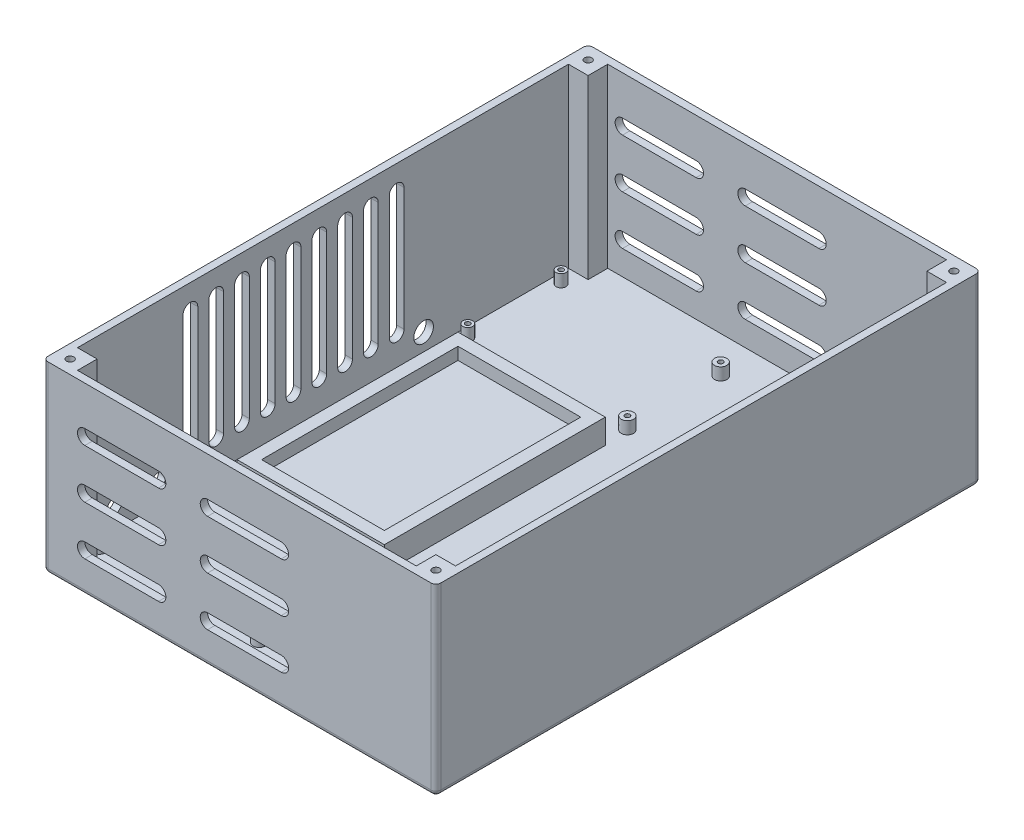
SolidWorks part; units mm, degrees
ref_plane "Front Plane" through (0, 0, 0) normal (0, 0, 1) x (1, 0, 0)
ref_plane "Top Plane" through (0, 0, 0) normal (0, 1, 0) x (1, 0, 0)
ref_plane "Right Plane" through (0, 0, 0) normal (1, 0, 0) x (0, 0, -1)
sketch "Sketch1" plane through (0, 0, 0) normal (0, 1, 0) x (1, 0, 0)
  line L1 (-80, 111) -> (80, 111)
  line L2 (-80, 111) -> (-80, -111)
  line L3 (-80, -111) -> (80, -111)
  line L4 (80, 111) -> (80, -111)
  line L5 (-80, 111) -> (80, -111) construction
  line L6 (-80, -111) -> (80, 111) construction
  point P0 (0, 0)
  dimension "D1" = 222
  dimension "D2" = 160
extrude "Boss-Extrude1" add sketch "Sketch1" along normal blind 75
sketch "Sketch2" plane through (0, 75, 0) normal (0, 1, 0) x (1, 0, 0)
  line L0 (80, -111) -> (80, 111) construction
  line L1 (-77, 108) -> (77, 108)
  line L2 (-77, 108) -> (-77, -108)
  line L3 (-77, -108) -> (77, -108)
  line L4 (77, 108) -> (77, -108)
  line L5 (-77, 108) -> (77, -108) construction
  line L6 (-77, -108) -> (77, 108) construction
  line L7 (80, 111) -> (-80, 111) construction
  point P0 (0, 0)
  point P6 (77, 0)
  point P9 (80, 0)
  point P12 (0, 111)
  point P13 (0, 108)
  dimension "D1" = 3
  dimension "D2" = 3
extrude "Cut-Extrude1" cut sketch "Sketch2" against normal offset from surface (72 mm away) 3 up to face at (0, 0, 0)
sketch "Sketch3" plane through (0, 3, 0) normal (0, 1, 0) x (1, 0, 0)
  line L0 (-77, -108) -> (-77, 108) construction
  line L1 (-77, -108) -> (77, -108) construction
  line L2 (-77, 108) -> (77, 108) construction
  line L3 (77, 108) -> (77, -108) construction
  line L5 (77, -108) -> (-77, -108) construction
  circle A0 centre (-73, -95) radius 2
  circle A1 centre (-73, -57.5) radius 2
  circle A2 centre (-73, 55) radius 2
  circle A3 centre (-73, 93) radius 2
  circle A4 centre (63, -94) radius 2.5
  circle A7 centre (63, 94) radius 2.5
  circle A8 centre (-8, -95) radius 2.5
  circle A9 centre (-8, -57) radius 2.5
  circle A10 centre (-8, 55) radius 2.5
  circle A11 centre (-8, 93) radius 2.5
  circle A12 centre (13.5372, 0.0714) radius 2.5
  circle A13 centre (68.2586, 5.3449) radius 2.5
  circle A14 centre (-73, -95) radius 1
  circle A15 centre (-73, -57.5) radius 1
  circle A16 centre (-73, 55) radius 1
  circle A17 centre (-73, 93) radius 1
  circle A18 centre (-8, -95) radius 1
  circle A19 centre (-8, -57) radius 1
  circle A20 centre (-8, 55) radius 1
  circle A21 centre (-8, 93) radius 1
  circle A22 centre (13.5372, 0.0714) radius 1
  circle A23 centre (63, -94) radius 1
  circle A24 centre (68.2586, 5.3449) radius 1
  circle A25 centre (63, 94) radius 1
  dimension "D2" = 4
  dimension "D3" = 5
  dimension "D22" = 2
  dimension "D1" = 4
  dimension "D4" = 37.5
  dimension "D5" = 38
  dimension "D6" = 13
  dimension "D7" = 15
  dimension "D8" = 14
  dimension "D9" = 14
  dimension "D10" = 14
  dimension "D11" = 13
  dimension "D12" = 65
  dimension "D13" = 38
  dimension "D14" = 65
  dimension "D15" = 38
  dimension "D16" = 15
  dimension "D17" = 61
  dimension "D18" = 59
  dimension "D19" = 98.5
  dimension "D20" = 91
  dimension "D21" = 14
extrude "Boss-Extrude2" add sketch "Sketch3" along normal blind 5
sketch "Sketch4" plane through (0, 3, 0) normal (0, 1, 0) x (1, 0, 0)
  line L0 (-77, -108) -> (-77, -100)
  line L1 (-77, -108) -> (-77, 108) construction
  line L2 (-77, -100) -> (-69, -100)
  line L3 (-69, -100) -> (-69, -108)
  line L4 (-77, -108) -> (77, -108) construction
  line L5 (-69, -108) -> (-77, -108)
  line L6 (-77, 108) -> (-77, 100)
  line L7 (-77, 100) -> (-69, 100)
  line L8 (-69, 100) -> (-69, 108)
  line L9 (77, 108) -> (-77, 108) construction
  line L10 (-69, 108) -> (-77, 108)
  line L11 (77, 108) -> (69, 108)
  line L12 (69, 108) -> (69, 100)
  line L13 (69, 100) -> (77, 100)
  line L14 (77, 108) -> (77, -108) construction
  line L15 (77, 100) -> (77, 108)
  line L16 (77, -108) -> (77, -100)
  line L17 (77, -100) -> (69, -100)
  line L18 (69, -100) -> (69, -108)
  line L19 (69, -108) -> (77, -108)
  dimension "D1" = 8
  dimension "D2" = 8
  dimension "D3" = 8
  dimension "D4" = 8
  dimension "D5" = 8
  dimension "D6" = 8
  dimension "D7" = 8
  dimension "D8" = 8
extrude "Boss-Extrude3" add sketch "Sketch4" along normal up to surface (72 mm away) up to face at (0, 75, 0)
sketch "Sketch5" plane through (0, 75, 0) normal (0, 1, 0) x (1, 0, 0)
  line L0 (-80, 111) -> (-80, -111) construction
  line L1 (80, 111) -> (-80, 111) construction
  line L2 (80, -111) -> (80, 111) construction
  line L3 (-80, -111) -> (80, -111) construction
  circle A0 centre (-74.5, 105.5) radius 1.5
  circle A1 centre (74.5, 105.5) radius 1.5
  circle A2 centre (74.5, -105.5) radius 1.5
  circle A3 centre (-74.5, -105.5) radius 1.5
  point P8 (0, 0)
  point P9 (0, 0)
  point P10 (0, 0)
  point P11 (0, 0)
  dimension "D1" = 3
  dimension "D2" = 5.5
  dimension "D3" = 5.5
  dimension "D4" = 5.5
  dimension "D5" = 5.5
sketch "Sketch6" plane through (-77, 0, 0) normal (1, 0, 0) x (0, 0, -1)
  line L0 (-100, 75) -> (-100, 3) construction
  line L5 (-91, 15) -> (-79, 15)
  line L6 (-91, 15) -> (-91, 8)
  line L11 (-91, 8) -> (-79, 8)
  line L12 (-79, 15) -> (-79, 8)
  line L13 (-91, 15) -> (-79, 8) construction
  line L14 (-91, 8) -> (-79, 15) construction
  line L15 (-73, 15) -> (-61, 15)
  line L16 (-73, 15) -> (-73, 8)
  line L17 (-73, 8) -> (-61, 8)
  line L18 (-61, 15) -> (-61, 8)
  line L19 (-73, 15) -> (-61, 8) construction
  line L20 (-73, 8) -> (-61, 15) construction
  line L21 (-100, 3) -> (100, 3) construction
  circle A0 centre (-67, 11.5) radius 3
  circle A1 centre (-85, 11.5) radius 3
  point P0 (-85, 11.5)
  point P5 (-67, 11.5)
  point P11 (-79, 11.5)
  point P12 (-73, 11.5)
  point P13 (-91, 11.5)
  point P16 (-85, 8)
  dimension "D8" = 6
  dimension "D9" = 6
  dimension "D1" = 7
  dimension "D2" = 12
  dimension "D3" = 12
  dimension "D4" = 7
  dimension "D5" = 6
  dimension "D6" = 9
  dimension "D7" = 5
fillet "Fillet4" radius 2 8 edges at (80, 37.5, 111) (-80, 37.5, 111) (-80, 37.5, -111) (80, 37.5, -111) (80, 0, 0) (0, 0, 111) (-80, 0, 0) (0, 0, -111)
extrude "Cut-Extrude3" cut sketch "Sketch5" against normal blind 25
sketch "Sketch7" plane through (-80, 0, 0) normal (-1, 0, 0) x (0, 0, 1)
  line L0 (-111, 2) -> (-111, 75) construction
  line L3 (-30, 65) -> (-30, 15) construction
  line L8 (-27, 65) -> (-27, 15)
  line L11 (-33, 65) -> (-33, 15)
  line L14 (-9, 65) -> (-9, 15) construction
  line L17 (-6, 65) -> (-6, 15)
  line L20 (-12, 65) -> (-12, 15)
  line L23 (12, 65) -> (12, 15) construction
  line L26 (15, 65) -> (15, 15)
  line L29 (9, 65) -> (9, 15)
  line L32 (22.5, 65) -> (22.5, 15) construction
  line L35 (25.5, 65) -> (25.5, 15)
  line L36 (19.5, 65) -> (19.5, 15)
  line L37 (33, 65) -> (33, 15) construction
  line L38 (36, 65) -> (36, 15)
  line L39 (30, 65) -> (30, 15)
  line L40 (43.5, 65) -> (43.5, 15) construction
  line L41 (46.5, 65) -> (46.5, 15)
  line L42 (40.5, 65) -> (40.5, 15)
  line L43 (-19.5, 65) -> (-19.5, 15) construction
  line L44 (-16.5, 65) -> (-16.5, 15)
  line L45 (-22.5, 65) -> (-22.5, 15)
  line L46 (-109, 2) -> (109, 2) construction
  line L49 (1.5, 65) -> (1.5, 15) construction
  line L50 (4.5, 65) -> (4.5, 15)
  line L51 (-1.5, 65) -> (-1.5, 15)
  line L52 (54, 65) -> (54, 15) construction
  line L53 (57, 65) -> (57, 15)
  line L54 (51, 65) -> (51, 15)
  arc A22 (-27, 65) -> (-33, 65) centre (-30, 65) ccw
  arc A23 (-33, 15) -> (-27, 15) centre (-30, 15) ccw
  arc A24 (-6, 65) -> (-12, 65) centre (-9, 65) ccw
  arc A25 (-12, 15) -> (-6, 15) centre (-9, 15) ccw
  arc A26 (15, 65) -> (9, 65) centre (12, 65) ccw
  arc A27 (9, 15) -> (15, 15) centre (12, 15) ccw
  arc A28 (25.5, 65) -> (19.5, 65) centre (22.5, 65) ccw
  arc A29 (19.5, 15) -> (25.5, 15) centre (22.5, 15) ccw
  arc A30 (36, 65) -> (30, 65) centre (33, 65) ccw
  arc A31 (30, 15) -> (36, 15) centre (33, 15) ccw
  arc A32 (46.5, 65) -> (40.5, 65) centre (43.5, 65) ccw
  arc A33 (40.5, 15) -> (46.5, 15) centre (43.5, 15) ccw
  arc A34 (-16.5, 65) -> (-22.5, 65) centre (-19.5, 65) ccw
  arc A35 (-22.5, 15) -> (-16.5, 15) centre (-19.5, 15) ccw
  arc A38 (4.5, 65) -> (-1.5, 65) centre (1.5, 65) ccw
  arc A39 (-1.5, 15) -> (4.5, 15) centre (1.5, 15) ccw
  arc A40 (57, 65) -> (51, 65) centre (54, 65) ccw
  arc A41 (51, 15) -> (57, 15) centre (54, 15) ccw
  circle A42 centre (-41, 10) radius 4
  point P4 (-33, 40)
  point P12 (-30, 40)
  point P19 (-9, 40)
  point P26 (12, 40)
  point P33 (22.5, 40)
  point P40 (33, 40)
  point P47 (43.5, 40)
  point P54 (-19.5, 40)
  point P68 (1.5, 40)
  point P75 (54, 40)
  dimension "D11" = 3
  dimension "D12" = 3
  dimension "D13" = 3
  dimension "D14" = 3
  dimension "D15" = 3
  dimension "D16" = 3
  dimension "D17" = 3
  dimension "D19" = 38
  dimension "D21" = 3
  dimension "D33" = 3
  dimension "D20" = 8
  dimension "D4" = 81
  dimension "D7" = 50
  dimension "D5" = 50
  dimension "D6" = 50
  dimension "D8" = 50
  dimension "D9" = 50
  dimension "D10" = 50
  dimension "D18" = 50
  dimension "D22" = 50
  dimension "D23" = 8
  dimension "D24" = 8
  dimension "D25" = 10.5
  dimension "D26" = 10.5
  dimension "D27" = 10.5
  dimension "D28" = 10.5
  dimension "D29" = 10.5
  dimension "D30" = 10.5
  dimension "D31" = 10.5
  dimension "D32" = 50
  dimension "D34" = 10.5
sketch "Sketch8" plane through (0, 0, 111) normal (0, 0, 1) x (1, 0, 0)
  line L0 (-63, 56) -> (-33, 56) construction
  line L1 (-63, 59) -> (-33, 59)
  line L2 (-63, 53) -> (-33, 53)
  line L3 (-13, 56) -> (17, 56) construction
  line L4 (-13, 59) -> (17, 59)
  line L5 (-13, 53) -> (17, 53)
  line L6 (-63, 36) -> (-33, 36) construction
  line L7 (-63, 39) -> (-33, 39)
  line L8 (-63, 33) -> (-33, 33)
  line L9 (17, 36) -> (-13, 36) construction
  line L10 (17, 33) -> (-13, 33)
  line L11 (17, 39) -> (-13, 39)
  line L12 (-63, 16) -> (-33, 16) construction
  line L13 (-63, 19) -> (-33, 19)
  line L14 (-63, 13) -> (-33, 13)
  line L15 (-13, 16) -> (17, 16) construction
  line L16 (-13, 19) -> (17, 19)
  line L17 (-13, 13) -> (17, 13)
  line L18 (-78, 75) -> (-78, 2) construction
  line L20 (-80, 0) -> (80, 0) construction
  arc A0 (-63, 59) -> (-63, 53) centre (-63, 56) ccw
  arc A1 (-33, 53) -> (-33, 59) centre (-33, 56) ccw
  arc A2 (-13, 59) -> (-13, 53) centre (-13, 56) ccw
  arc A3 (17, 53) -> (17, 59) centre (17, 56) ccw
  arc A4 (-63, 39) -> (-63, 33) centre (-63, 36) ccw
  arc A5 (-33, 33) -> (-33, 39) centre (-33, 36) ccw
  arc A6 (17, 33) -> (17, 39) centre (17, 36) ccw
  arc A7 (-13, 39) -> (-13, 33) centre (-13, 36) ccw
  arc A8 (-63, 19) -> (-63, 13) centre (-63, 16) ccw
  arc A9 (-33, 13) -> (-33, 19) centre (-33, 16) ccw
  arc A10 (-13, 19) -> (-13, 13) centre (-13, 16) ccw
  arc A11 (17, 13) -> (17, 19) centre (17, 16) ccw
  point P2 (-48, 56)
  point P8 (2, 56)
  point P15 (-48, 36)
  point P22 (2, 36)
  point P29 (-48, 16)
  point P36 (2, 16)
  dimension "D5" = 3
  dimension "D6" = 3
  dimension "D7" = 3
  dimension "D8" = 3
  dimension "D11" = 3
  dimension "D12" = 3
  dimension "D1" = 30
  dimension "D2" = 30
  dimension "D3" = 30
  dimension "D4" = 30
  dimension "D9" = 30
  dimension "D10" = 30
  dimension "D13" = 50
  dimension "D14" = 30
  dimension "D15" = 16
  dimension "D16" = 20
  dimension "D17" = 20
extrude "Cut-Extrude8" cut sketch "Sketch8" against normal up to surface (3 mm away) up to face at (0, 39, 108)
sketch "Sketch9" plane through (0, 0, -111) normal (0, 0, -1) x (-1, 0, 0)
  line L0 (-17, 56) -> (13, 56) construction
  line L1 (-17, 59) -> (13, 59)
  line L2 (-17, 53) -> (13, 53)
  line L3 (33, 56) -> (63, 56) construction
  line L4 (33, 59) -> (63, 59)
  line L5 (33, 53) -> (63, 53)
  line L6 (-17, 36) -> (13, 36) construction
  line L7 (-17, 39) -> (13, 39)
  line L8 (-17, 33) -> (13, 33)
  line L9 (33, 36) -> (63, 36) construction
  line L10 (33, 39) -> (63, 39)
  line L11 (33, 33) -> (63, 33)
  line L12 (-17, 16) -> (13, 16) construction
  line L13 (-17, 19) -> (13, 19)
  line L14 (-17, 13) -> (13, 13)
  line L15 (33, 16) -> (63, 16) construction
  line L16 (33, 19) -> (63, 19)
  line L17 (33, 13) -> (63, 13)
  line L18 (78, 2) -> (78, 75) construction
  line L20 (80, 0) -> (-80, 0) construction
  arc A0 (-17, 59) -> (-17, 53) centre (-17, 56) ccw
  arc A1 (13, 53) -> (13, 59) centre (13, 56) ccw
  arc A2 (33, 59) -> (33, 53) centre (33, 56) ccw
  arc A3 (63, 53) -> (63, 59) centre (63, 56) ccw
  arc A4 (-17, 39) -> (-17, 33) centre (-17, 36) ccw
  arc A5 (13, 33) -> (13, 39) centre (13, 36) ccw
  arc A6 (33, 39) -> (33, 33) centre (33, 36) ccw
  arc A7 (63, 33) -> (63, 39) centre (63, 36) ccw
  arc A8 (-17, 19) -> (-17, 13) centre (-17, 16) ccw
  arc A9 (13, 13) -> (13, 19) centre (13, 16) ccw
  arc A10 (33, 19) -> (33, 13) centre (33, 16) ccw
  arc A11 (63, 13) -> (63, 19) centre (63, 16) ccw
  point P2 (-2, 56)
  point P8 (48, 56)
  point P15 (-2, 36)
  point P22 (48, 36)
  point P29 (-2, 16)
  point P36 (48, 16)
  point P42 (0, 0)
  point P43 (0, 0)
  point P44 (0, 0)
  point P45 (0, 0)
  point P46 (0, 0)
  dimension "D7" = 3
  dimension "D8" = 3
  dimension "D9" = 3
  dimension "D10" = 3
  dimension "D11" = 3
  dimension "D12" = 3
  dimension "D1" = 30
  dimension "D2" = 30
  dimension "D3" = 30
  dimension "D4" = 30
  dimension "D5" = 30
  dimension "D6" = 30
  dimension "D13" = 30
  dimension "D14" = 50
  dimension "D15" = 16
  dimension "D16" = 20
  dimension "D17" = 20
extrude "Cut-Extrude10" cut sketch "Sketch9" against normal up to surface (3 mm away) up to face at (0, 39, -108)
sketch "Sketch10" plane through (0, 3, 0) normal (0, 1, 0) x (1, 0, 0)
  line L0 (-77, -100) -> (-77, 100) construction
  line L1 (-67, -45) -> (-7, -45)
  line L2 (-67, -45) -> (-67, 45)
  line L3 (-67, 45) -> (-7, 45)
  line L4 (-7, -45) -> (-7, 45)
  line L5 (-67, -45) -> (-7, 45) construction
  line L6 (-67, 45) -> (-7, -45) construction
  point P0 (-37, 0)
  point P5 (0, 0)
  dimension "D1" = 90
  dimension "D2" = 60
  dimension "D3" = 40
extrude "Boss-Extrude5" add sketch "Sketch10" along normal blind 5
sketch "Sketch12" plane through (0, 8, 0) normal (0, 1, 0) x (1, 0, 0)
  line L0 (-77, -100) -> (-77, 100) construction
  line L1 (-62, -40) -> (-12, -40)
  line L2 (-62, -40) -> (-62, 40)
  line L3 (-62, 40) -> (-12, 40)
  line L4 (-12, -40) -> (-12, 40)
  line L5 (-62, -40) -> (-12, 40) construction
  line L6 (-62, 40) -> (-12, -40) construction
  point P0 (-37, 0)
  point P6 (0, 0)
  point P9 (-77, 0)
  line M5 (-7, -45) -> (-7, 45)
  line M6 (-7, 45) -> (-67, 45)
  line M7 (-67, 45) -> (-67, -45)
  line M8 (-67, -45) -> (-7, -45)
  dimension "D1" = 50
  dimension "D2" = 80
  dimension "D3" = 40
extrude "Boss-Extrude6" add sketch "Sketch12" along normal blind 5 contours L4 L1 L2 L3 M8 M5 M6 M7
extrude "Cut-Extrude14" cut sketch "Sketch6" against normal up to surface (3 mm away) contours A1 | A0 up to face at (-80, 38.5, 0)
extrude "Cut-Extrude15" cut sketch "Sketch7" against normal up to surface (3 mm away) up to face at (-77, 11.5, 82)
